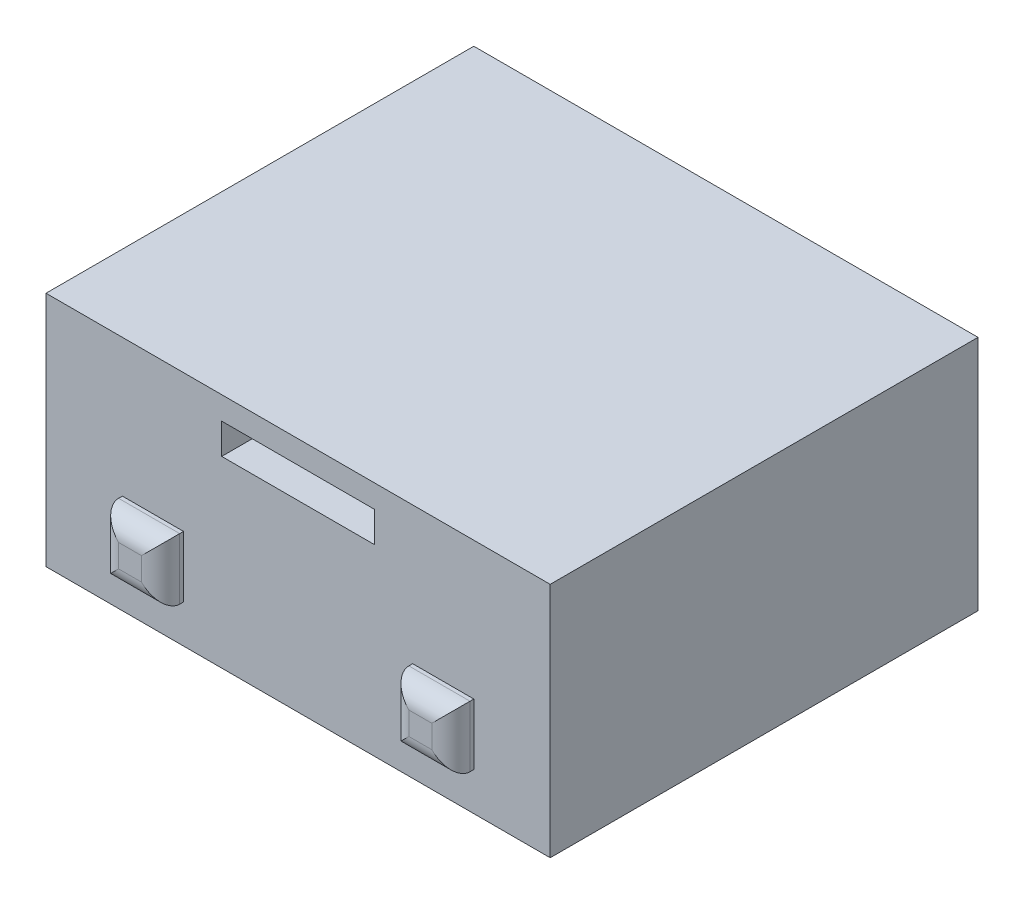
SolidWorks part; units mm, degrees
ref_plane "Front Plane" through (0, 0, 0) normal (0, 0, 1) x (1, 0, 0)
ref_plane "Top Plane" through (0, 0, 0) normal (0, 1, 0) x (1, 0, 0)
ref_plane "Right Plane" through (0, 0, 0) normal (1, 0, 0) x (0, 0, -1)
sketch "Sketch1" plane through (0, 0, 0) normal (0, 1, 0) x (1, 0, 0)
  line L1 (-33, -28) -> (33, -28)
  line L2 (-33, -28) -> (-33, 28)
  line L3 (-33, 28) -> (33, 28)
  line L4 (33, -28) -> (33, 28)
  line L5 (-33, -28) -> (33, 28) construction
  line L6 (-33, 28) -> (33, -28) construction
  point P0 (0, 0)
  dimension "D1" = 66
  dimension "D2" = 56
extrude "Base" add sketch "Sketch1" against normal blind 3
sketch "Sketch4" plane through (0, 0, 0) normal (0, 1, 0) x (1, 0, 0)
  line L1 (-33, 28) -> (33, 28)
  line L2 (-33, 28) -> (-33, -28)
  line L3 (-33, -28) -> (33, -28)
  line L4 (33, 28) -> (33, -28)
  line L5 (-33, 28) -> (33, -28) construction
  line L6 (-33, -28) -> (33, 28) construction
  line L7 (-29, 24) -> (29, 24)
  line L8 (-29, 24) -> (-29, -24)
  line L9 (-29, -24) -> (29, -24)
  line L10 (29, 24) -> (29, -24)
  line L11 (-29, 24) -> (29, -24) construction
  line L12 (-29, -24) -> (29, 24) construction
  point P0 (0, 0)
  point P7 (0, 0)
  dimension "D1" = 48
  dimension "D2" = 58
extrude "Wall1" add sketch "Sketch4" against normal blind 21
sketch "Sketch8" plane through (0, 0, 0) normal (0, 1, 0) x (1, 0, 0)
  line L1 (-31, 26) -> (31, 26)
  line L2 (-31, 26) -> (-31, -26)
  line L3 (-31, -26) -> (31, -26)
  line L4 (31, 26) -> (31, -26)
  line L5 (-31, 26) -> (31, -26) construction
  line L6 (-31, -26) -> (31, 26) construction
  line L7 (-29, 24) -> (29, 24)
  line L8 (-29, 24) -> (-29, -24)
  line L9 (-29, -24) -> (29, -24)
  line L10 (29, 24) -> (29, -24)
  line L11 (-29, 24) -> (29, -24) construction
  line L12 (-29, -24) -> (29, 24) construction
  point P0 (0, 0)
  point P6 (0, 0)
  dimension "D1" = 52
  dimension "D2" = 62
extrude "Wall2" cut sketch "Sketch8" along normal blind 2 from surface at -21 starting at face at (0, -21, 0)
sketch "Sketch9" plane through (0, 0, 0) normal (0, 1, 0) x (1, 0, 0)
  line L1 (-24, 19) -> (24, 19)
  line L2 (-24, 19) -> (-24, -19)
  line L3 (-24, -19) -> (24, -19)
  line L4 (24, 19) -> (24, -19)
  line L5 (-24, 19) -> (24, -19) construction
  line L6 (-24, -19) -> (24, 19) construction
  line L7 (-22, 17) -> (22, 17)
  line L8 (-22, 17) -> (-22, -17)
  line L9 (-22, -17) -> (22, -17)
  line L10 (22, 17) -> (22, -17)
  line L11 (-22, 17) -> (22, -17) construction
  line L12 (-22, -17) -> (22, 17) construction
  point P1 (0, 0)
  point P6 (0, 0)
  dimension "D1" = 38
  dimension "D2" = 48
  dimension "D3" = 34
  dimension "D4" = 44
extrude "PCBWall" add sketch "Sketch9" against normal blind 4 from surface at -3 starting at face at (0, -3, 0)
sketch "Sketch10" plane through (0, 0, 0) normal (0, 1, 0) x (1, 0, 0)
  line L0 (22, 13.1) -> (14.7, 13.1) construction
  line L1 (22, 17) -> (22, -17) construction
  line L2 (14.7, 13.1) -> (14.7, 17) construction
  line L3 (-22, 17) -> (22, 17) construction
  circle A0 centre (14.7, 13.1) radius 1.2
  dimension "D1" = 2.4
  dimension "D2" = 7.3
  dimension "D3" = 3.9
extrude "Mounting hole" cut sketch "Sketch10" against normal blind 4
sketch "Sketch11" plane through (0, 0, 0) normal (0, 1, 0) x (1, 0, 0)
  line L1 (-33, 28) -> (33, 28)
  line L2 (-33, 28) -> (-33, -28)
  line L3 (-33, -28) -> (33, -28)
  line L4 (33, 28) -> (33, -28)
  line L5 (-33, 28) -> (33, -28) construction
  line L6 (-33, -28) -> (33, 28) construction
  point P0 (0, 0)
extrude "Extended Base" add sketch "Sketch11" along normal blind 10
sketch "Sketch12" plane through (0, 0, 0) normal (0, 0, 1) x (1, 0, 0)
  line L0 (0, 0) -> (0, 10) construction
  line L1 (-33, 10) -> (33, 10) construction
  line L2 (-33, 10) -> (0, 5) construction
  line L3 (0, 5) -> (33, 10) construction
  line L5 (-10, 3) -> (10, 3)
  line L6 (-10, 3) -> (-10, 7)
  line L7 (-10, 7) -> (10, 7)
  line L8 (10, 3) -> (10, 7)
  line L9 (-10, 3) -> (10, 7) construction
  line L10 (-10, 7) -> (10, 3) construction
  dimension "D1" = 20
  dimension "D2" = 4
extrude "Head Band Slot" cut sketch "Sketch12" against normal through all from surface at 28 starting at face at (0, -5.5, 28)
sketch "Sketch13" plane through (0, 0, 0) normal (0, 0, 1) x (1, 0, 0)
  line L0 (0, -21) -> (0, -12) construction
  line L1 (-33, -21) -> (33, -21) construction
  line L2 (0, -12) -> (-19, -12) construction
  line L3 (0, -12) -> (19, -12) construction
  line L5 (-23, -16) -> (-15, -16)
  line L6 (-23, -16) -> (-23, -8)
  line L7 (-23, -8) -> (-15, -8)
  line L8 (-15, -16) -> (-15, -8)
  line L9 (-23, -16) -> (-15, -8) construction
  line L10 (-23, -8) -> (-15, -16) construction
  line L11 (15, -16) -> (23, -16)
  line L12 (15, -16) -> (15, -8)
  line L13 (15, -8) -> (23, -8)
  line L14 (23, -16) -> (23, -8)
  line L15 (15, -16) -> (23, -8) construction
  line L16 (15, -8) -> (23, -16) construction
  dimension "D1" = 9
  dimension "D2" = 19
  dimension "D3" = 19
  dimension "D4" = 8
  dimension "D5" = 8
  dimension "D6" = 8
  dimension "D7" = 8
extrude "Clips" add sketch "Sketch13" along normal blind 3 from surface at 28 starting at face at (0, -5.5, 28)
mirror "Clips2" about plane through (0, 0, 0) normal (0, 0, 1) of "Clips"
fillet "Fillet2" radius 2.5 16 edges at (-19, -16, -31) (-15, -12, -31) (-19, -8, -31) (-23, -12, -31) (19, -16, -31) (23, -12, -31) (19, -8, -31) (15, -12, -31) (-19, -8, 31) (-15, -12, 31) (-19, -16, 31) (-23, -12, 31) (19, -8, 31) (23, -12, 31) (19, -16, 31) (15, -12, 31)
sketch "ElectrodeHeaderPoint" plane through (0, 0, 0) normal (0, 1, 0) x (1, 0, 0)
  line L0 (19.8, 24) -> (19.8, 14.5) construction
  line L1 (29, 24) -> (-29, 24) construction
  line L2 (29, 14.5) -> (19.8, 14.5) construction
  line L3 (29, -24) -> (29, 24) construction
  point P8 (0, 0)
  dimension "D1" = 9.5
  dimension "D2" = 9.2
